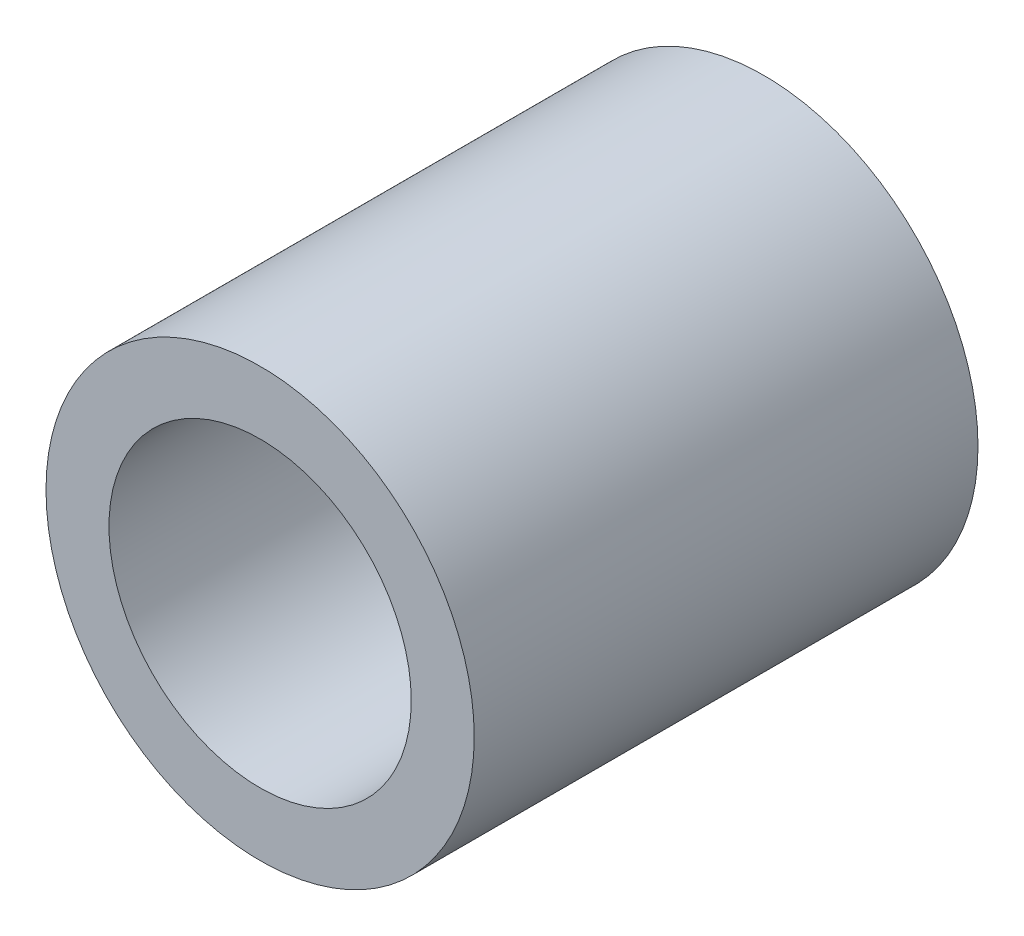
SolidWorks part; units mm, degrees
ref_plane "Front Plane" through (0, 0, 0) normal (1, 0, 0) x (0, 1, 0)
ref_plane "Top Plane" through (0, 0, 0) normal (0, 0, 1) x (0, 1, 0)
ref_plane "Right Plane" through (0, 0, 0) normal (0, 1, 0) x (-1, 0, 0)
sketch "Sketch1" plane through (0, 0, 0) normal (0, 0, 1) x (0, 1, 0)
  circle A0 centre (0, 0) radius 7.62
  circle A1 centre (0, 0) radius 10.795
  dimension "D1" = 3.175
  dimension "D2" = 15.24
extrude "Boss-Extrude1" add sketch "Sketch1" along normal blind 25.4
